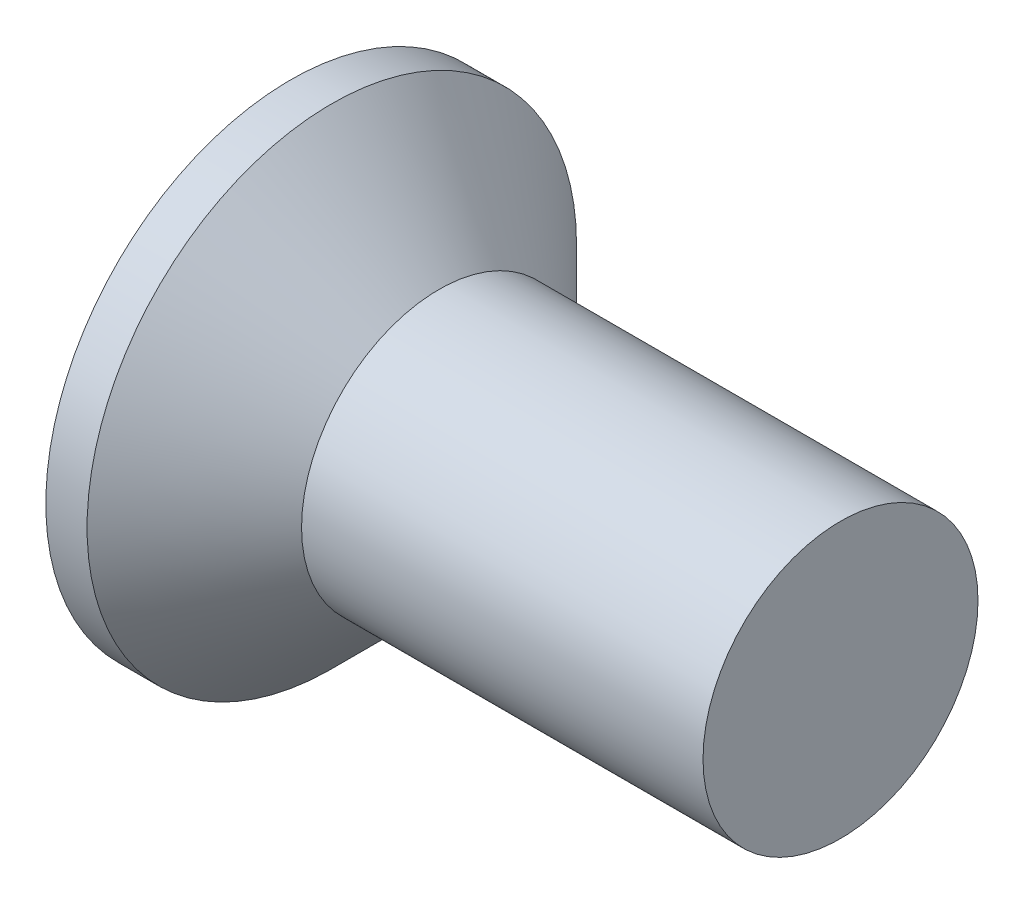
SolidWorks part; units mm, degrees
ref_plane "Front" through (0, 0, 0) normal (0, 0, 1) x (1, 0, 0)
ref_plane "Top" through (0, 0, 0) normal (0, 1, 0) x (1, 0, 0)
ref_plane "Right" through (0, 0, 0) normal (1, 0, 0) x (0, 0, -1)
sketch "Sketch1" plane through (0, 0, 0) normal (0, 0, 1) x (1, 0, 0)
  line L0 (10, 2.5) -> (4.3, 2.5)
  line L1 (4.3, 2.5) -> (2.7, 2.5)
  line L2 (2.7, 2.5) -> (0.75, 4.45)
  line L3 (0.75, 4.45) -> (0, 4.45)
  line L4 (10, 2.5) -> (10, 0)
  line L5 (4.5158, 0) -> (-89.8219, 0) construction
  line L6 (10, 0) -> (0, 0)
  line L7 (0, 4.45) -> (0, 0)
  dimension "d" = 5
  dimension "D1" = 45
  dimension "dk" = 8.9
  dimension "k" = 2.7
  dimension "l" = 10
  dimension "a" = 1.6
revolve "Base" add sketch "Sketch1" angle 360 about L5
cosmetic thread "ThreadCosmetic1" [suppressed] parameters "bb"=7.3, "THD_MINOR"=4.134
sketch "Sketch6" plane through (0, 0, 0) normal (1, 0, 0) x (0, 0, -1)
  line L0 (-1.9271, 0) -> (2.0512, 0) construction
  line L1 (0, 1.8651) -> (0, -2.0207) construction
  line L2 (0.52, 0.52) -> (0.52, 2.6)
  line L3 (0.52, 2.6) -> (-0.52, 2.6)
  line L4 (-0.52, 0.52) -> (-0.52, 2.6)
  line L5 (0.52, 0.52) -> (2.6, 0.52)
  line L6 (2.6, 0.52) -> (2.6, -0.52)
  line L7 (-2.6, 0.52) -> (-2.6, -0.52)
  line L8 (-0.52, 0.52) -> (-2.6, 0.52)
  line L9 (-0.52, -0.52) -> (-2.6, -0.52)
  line L10 (0.52, -0.52) -> (2.6, -0.52)
  line L11 (-0.52, -0.52) -> (-0.52, -2.6)
  line L12 (0.52, -2.6) -> (-0.52, -2.6)
  line L13 (0.52, -0.52) -> (0.52, -2.6)
  point P16 (-2.6, 0)
  point P17 (2.6, 0)
extrude "CrossRecess" cut sketch "Sketch6" along normal blind 1.35
draft "Draft9" type of draft neutral plane draft angle 30 faces to draft 4 face at (0.675, -2.6, 0) face at (0.675, 0, 2.6) face at (0.675, 0, -2.6) face at (0.675, 2.6, 0) neutral plane through (0, 4.45, 0) neutral plane normal (-1, 0, 0) parameters "D1"=30
fillet "Fillet5" radius 0.3 4 edges at (0.675, -0.52, -0.52) (0.675, -0.52, 0.52) (0.675, 0.52, -0.52) (0.675, 0.52, 0.52)
sketch "Sketch7" plane through (0, 0, 0) normal (1, 0, 0) x (0, 0, -1)
  line L0 (-2.0126, 0) -> (1.9757, 0) construction
  line L1 (0, 1.9314) -> (0, -2.0126) construction
  line L2 (0, 0) -> (1.5555, 1.5555) construction
  line L3 (0, 0.777) -> (1.8385, 1.8385)
  line L4 (-1.5402, 1.5402) -> (0, 0) construction
  line L5 (0.777, 0) -> (1.8385, 1.8385)
  line L6 (0, -0.777) -> (1.8385, -1.8385)
  line L7 (0.777, 0) -> (1.8385, -1.8385)
  line L8 (-0.777, 0) -> (-1.8385, -1.8385)
  line L9 (0, -0.777) -> (-1.8385, -1.8385)
  line L10 (-0.777, 0) -> (-1.8385, 1.8385)
  line L11 (0, 0.777) -> (-1.8385, 1.8385)
  dimension "D3" = 15
  dimension "m" = 5.2
extrude "Cut-Extrude3" [suppressed] cut sketch "Sketch7" along normal blind 10 draft 20
sketch "Sketch10" plane through (0, 0, 0) normal (0, 0, 1) x (1, 0, 0)
  line L0 (62.2289, 0) -> (-1.9277, 0) construction
  line L1 (2.7, 2.5) -> (3.5, 2.5)
  line L4 (3.5, 2.5) -> (3.5, 0)
  line L7 (3.5, 0) -> (2.7, 0)
  line L9 (2.7, 2.5) -> (0.75, 4.45) construction
  line L10 (2.7, 2.5) -> (2.7, 0)
  dimension "p" = 0.8
revolve "Revolve2" add sketch "Sketch10" angle 360 about L0
sketch "Sketch8" plane through (0, 0, 0) normal (0, 0, 1) x (1, 0, 0)
  line L0 (-28, 2.5) -> (-30, 2.067)
  line L1 (-30, 2.067) -> (5, 2.067)
  line L3 (10, -2.5) -> (10, 2.5) construction
  line L6 (5, 2.067) -> (5, 7.067)
  line L7 (5, 7.067) -> (-28, 7.067)
  line L8 (-28, 7.067) -> (-28, 2.5)
  line L9 (62.4753, 0) -> (52.9594, 0) construction
  dimension "D1" = 5
  dimension "x" = 2
  dimension "d" = 5
  dimension "THD_MINOR" = 4.134
  dimension "b" = 38
sketch "Sketch11" plane through (0, 0, 0) normal (0, 0, 1) x (1, 0, 0)
  line L0 (10, 2.125) -> (10.2165, 2.5)
  line L1 (10.2165, 2.5) -> (10.2165, 2.933)
  line L2 (10.2165, 2.933) -> (9.7835, 2.933)
  line L3 (9.7835, 2.933) -> (9.7835, 2.5)
  line L4 (9.7835, 2.5) -> (10, 2.125)
  line L5 (10, -2.5) -> (10, 2.5) construction
  line L6 (0, 0) -> (66.0064, 0) construction
  dimension "D1" = 5
  dimension "D2" = 0.433
revolve "Cut-Revolve10" [suppressed] cut sketch "Sketch11" angle 360 about L6
pattern_linear "LPattern10" [suppressed] count 14 spacing 0.5196 along (1, 0, 0)
equation "\"D1@Sketch6\" = \"m@Sketch6\" / 5"
equation "\"D1@CrossRecess\" = \"k@Sketch1\" / 2"
equation "\"D1@Sketch11\" = \"d@Sketch1\""
equation "\"D2@Sketch11\" =  ( \"d@Sketch1\" - \"THD_MINOR@ThreadCosmetic1\" )  / 2"
equation "\"D3@LPattern10\" = \"D2@Sketch11\" * 1.2"
equation "\"D1@LPattern10\" = \"bb@ThreadCosmetic1\" / \"D3@LPattern10\" "
